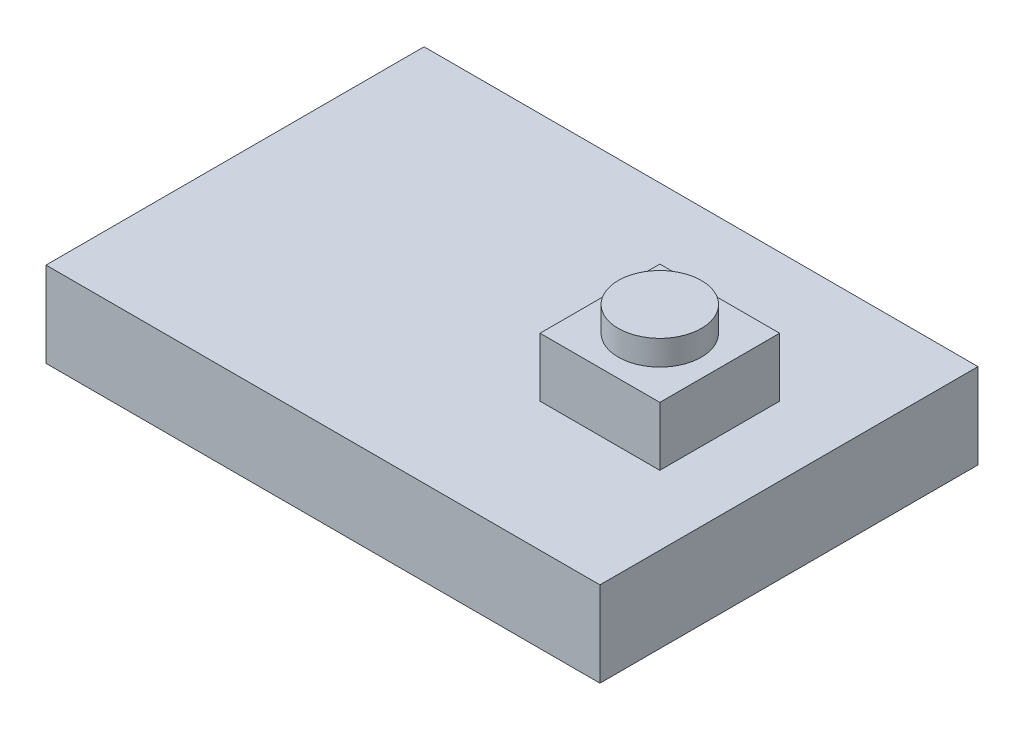
SolidWorks part; units mm, degrees
ref_plane "前视基准面" through (0, 0, 0) normal (0, 0, 1) x (1, 0, 0)
ref_plane "上视基准面" through (0, 0, 0) normal (0, 1, 0) x (1, 0, 0)
ref_plane "右视基准面" through (0, 0, 0) normal (1, 0, 0) x (0, 0, -1)
other "Configuration Table"
sketch "草图1" plane through (0, 0, 0) normal (0, 1, 0) x (1, 0, 0)
  line L1 (-20, 13.65) -> (20, 13.65)
  line L2 (-20, 13.65) -> (-20, -13.65)
  line L3 (-20, -13.65) -> (20, -13.65)
  line L4 (20, 13.65) -> (20, -13.65)
  line L5 (-20, 13.65) -> (20, -13.65) construction
  line L6 (-20, -13.65) -> (20, 13.65) construction
  point P0 (0, 0)
  dimension "D1" = 27.3
  dimension "D2" = 40
extrude "凸台-拉伸1" add sketch "草图1" along normal blind 6.15
sketch "草图2" plane through (0, 6.15, 0) normal (0, 1, 0) x (1, 0, 0)
  line L0 (20, -13.65) -> (20, 13.65) construction
  line L1 (6.35, 4.325) -> (15, 4.325)
  line L2 (6.35, 4.325) -> (6.35, -4.325)
  line L3 (6.35, -4.325) -> (15, -4.325)
  line L4 (15, 4.325) -> (15, -4.325)
  line L5 (6.35, 4.325) -> (15, -4.325) construction
  line L6 (6.35, -4.325) -> (15, 4.325) construction
  point P0 (10.675, 0)
  point P5 (0, 0)
  dimension "D1" = 8.65
  dimension "D2" = 5
extrude "凸台-拉伸2" add sketch "草图2" along normal blind 10.4 from surface at -6.15 starting at face at (0, 0, 0)
sketch "草图3" plane through (0, 10.4, 0) normal (0, 1, 0) x (1, 0, 0)
  line L0 (10.675, 0) -> (6.35, 0) construction
  line L1 (6.35, -4.325) -> (6.35, 4.325) construction
  line L2 (10.675, 0) -> (10.675, 4.325) construction
  line L3 (15, 4.325) -> (6.35, 4.325) construction
  circle A0 centre (10.675, 0) radius 3
  dimension "D1" = 6
extrude "凸台-拉伸3" add sketch "草图3" along normal blind 1.8
